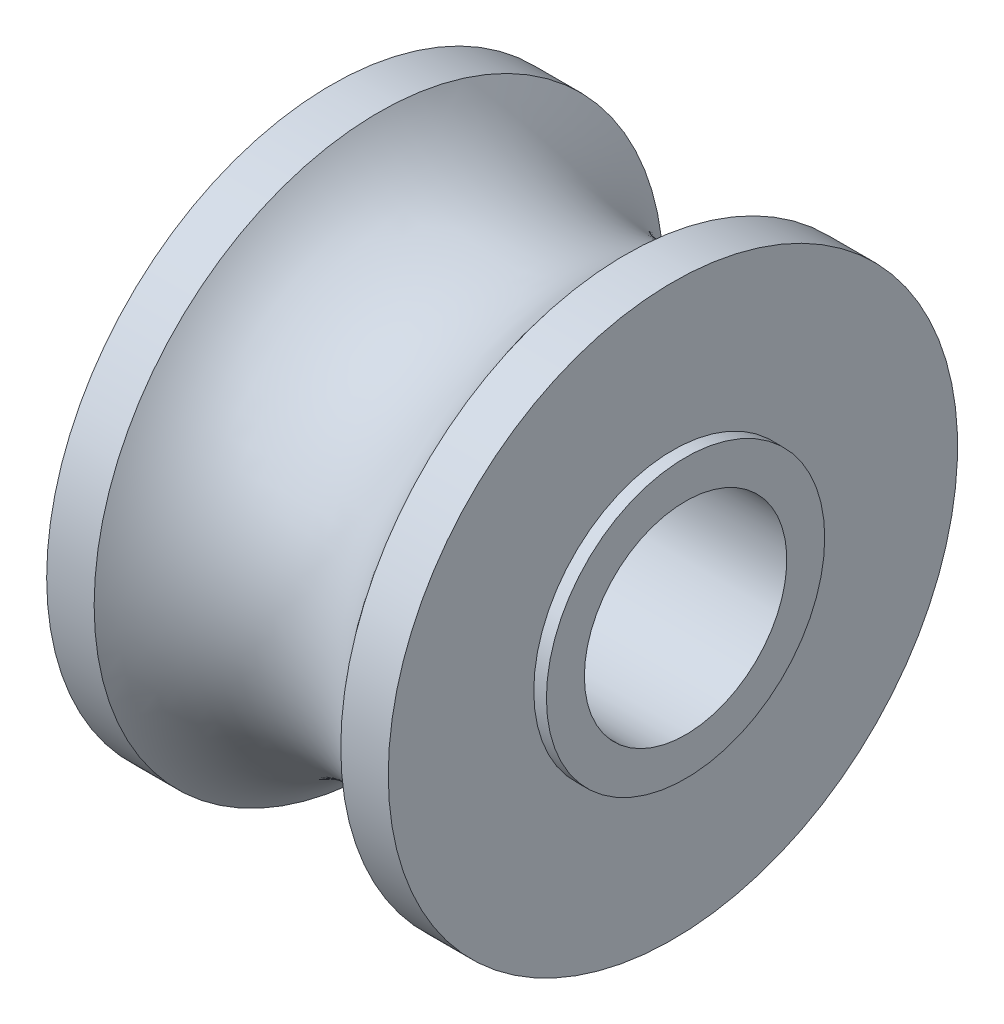
SolidWorks part; units mm, degrees
ref_plane "Front Plane" through (0, 0, 0) normal (0, 0, 1) x (1, 0, 0)
ref_plane "Top Plane" through (0, 0, 0) normal (0, 1, 0) x (1, 0, 0)
ref_plane "Right Plane" through (0, 0, 0) normal (1, 0, 0) x (0, 0, -1)
sketch "Sketch1" plane through (0, 0, 0) normal (0, 0, 1) x (1, 0, 0)
  line L0 (-7.25, 0) -> (7.25, 0) construction
  line L1 (-7.25, 4) -> (7.25, 4)
  line L2 (-7.25, 4) -> (-7.25, 5.5)
  line L3 (-7.25, 5.5) -> (-6.75, 5.5)
  line L4 (-6.75, 5.5) -> (-6.75, 11.25)
  line L5 (-6.75, 11.25) -> (-4.8734, 11.25)
  line L6 (0, 11.25) -> (0, 14.75) construction
  line L7 (0, 0) -> (0, 4) construction
  line L8 (7.25, 4) -> (-7.25, 4)
  line L9 (7.25, 4) -> (7.25, 5.5)
  line L10 (7.25, 5.5) -> (6.75, 5.5)
  line L11 (6.75, 5.5) -> (6.75, 11.25)
  line L12 (4.8734, 11.25) -> (6.75, 11.25)
  arc A0 (-4.8734, 11.25) -> (4.8734, 11.25) centre (0, 14.75) ccw
  point P4 (0, 0)
  point P8 (0, 8.75)
  dimension "D6" = 12
  dimension "D1" = 14.5
  dimension "D3" = 11
  dimension "D4" = 6.75
  dimension "D5" = 22.5
  dimension "D7" = 2.5
  dimension "D2" = 4
revolve "Revolve1" add sketch "Sketch1" angle 360 about L0
